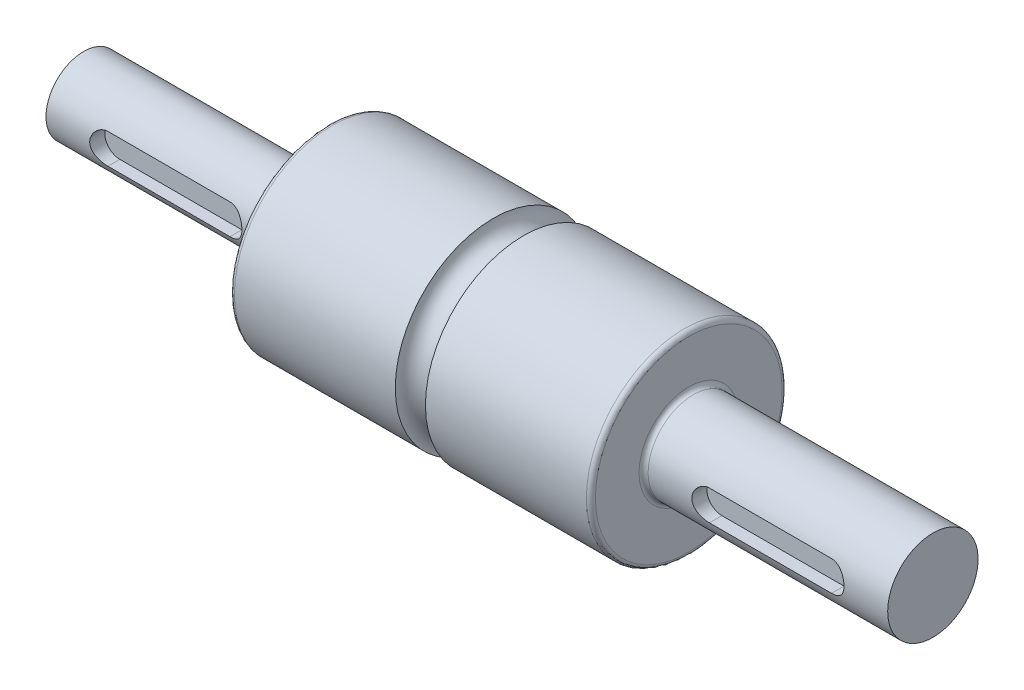
SolidWorks part; units mm, degrees
ref_plane "Alzado" through (0, 0, 0) normal (0, 0, 1) x (1, 0, 0)
ref_plane "Planta" through (0, 0, 0) normal (0, 1, 0) x (1, 0, 0)
ref_plane "Vista lateral" through (0, 0, 0) normal (1, 0, 0) x (0, 0, -1)
sketch "Croquis4" plane through (0, 0, 0) normal (0, 1, 0) x (1, 0, 0)
  line L0 (-140.9034, 0) -> (140.9034, 0) construction
  line L1 (-140.9034, 0) -> (-140.9034, 12.5)
  line L2 (-140.9034, 12.5) -> (-61.4034, 12.5)
  line L3 (-59.9034, 14) -> (-59.9034, 31)
  line L4 (-58.4034, 32.5) -> (-5, 32.5)
  line L5 (59.9034, 31) -> (59.9034, 16.5)
  line L6 (61.4034, 15) -> (140.9034, 15)
  line L7 (140.9034, 15) -> (140.9034, 0)
  line L8 (0, 76.976) -> (0, 0) construction
  line L9 (5, 32.5) -> (58.4034, 32.5)
  line L10 (-140.9034, 0) -> (140.9034, 0)
  arc A0 (-5, 32.5) -> (5, 32.5) centre (0, 32.5) ccw
  arc A1 (59.9034, 16.5) -> (61.4034, 15) centre (61.4034, 16.5) ccw
  arc A2 (58.4034, 32.5) -> (59.9034, 31) centre (58.4034, 31) cw
  arc A3 (-59.9034, 31) -> (-58.4034, 32.5) centre (-58.4034, 31) cw
  arc A4 (-61.4034, 12.5) -> (-59.9034, 14) centre (-61.4034, 14) ccw
  point P22 (-59.9034, 12.5)
  dimension "D5" = 5
  dimension "D6" = 1.5
  dimension "D1" = 81
  dimension "D2" = 12.5
  dimension "D3" = 15
  dimension "D4" = 32.5
revolve "Revolución2" add sketch "Croquis4" angle 360 about L10
sketch "Croquis5" plane through (0, 0, 0) normal (0, 0, 1) x (1, 0, 0)
  line L0 (-101.1534, 12.5) -> (-101.1534, -12.5) construction
  line L1 (-140.9034, 12.5) -> (-61.4034, 12.5) construction
  line L2 (-140.9034, 12.5) -> (-140.9034, -12.5) construction
  line L3 (-140.9034, -12.5) -> (-61.4034, -12.5) construction
  line L4 (-61.4034, 12.5) -> (-61.4034, -12.5) construction
  line L5 (-140.9034, 0) -> (-61.4034, 0) construction
  line L6 (0, 75.8836) -> (0, -70.4308) construction
  line L7 (-121.4034, -5) -> (-80.9034, -5)
  line L8 (121.4034, -5) -> (80.9034, -5)
  line L9 (-121.4034, 5) -> (-80.9034, 5)
  line L10 (121.4034, 5) -> (80.9034, 5)
  line L11 (-121.4034, -5) -> (-80.9034, 5) construction
  line L12 (-121.4034, 5) -> (-80.9034, -5) construction
  arc A0 (-121.4034, 5) -> (-121.4034, -5) centre (-121.4034, 0) ccw
  arc A1 (-80.9034, 5) -> (-80.9034, -5) centre (-80.9034, 0) cw
  arc A2 (80.9034, 5) -> (80.9034, -5) centre (80.9034, 0) ccw
  arc A3 (121.4034, 5) -> (121.4034, -5) centre (121.4034, 0) cw
  point P10 (-101.1534, 0)
  dimension "D1" = 40.5
  dimension "D2" = 10
extrude "Cortar-Extruir2" cut sketch "Croquis5" against normal blind 5 from offset 12.5 contours L7 A1 L9 A0
sketch "Croquis6" plane through (0, 0, 0) normal (0, 0, 1) x (1, 0, 0)
  line L0 (80.9034, 5) -> (121.4034, 5)
  line L1 (80.9034, -5) -> (121.4034, -5)
  line L2 (101.1534, 5) -> (101.1534, -5) construction
  arc A0 (80.9034, 5) -> (80.9034, -5) centre (80.9034, 0) ccw
  arc A1 (121.4034, 5) -> (121.4034, -5) centre (121.4034, 0) cw
extrude "Cortar-Extruir3" cut sketch "Croquis6" against normal blind 5 from offset 15
